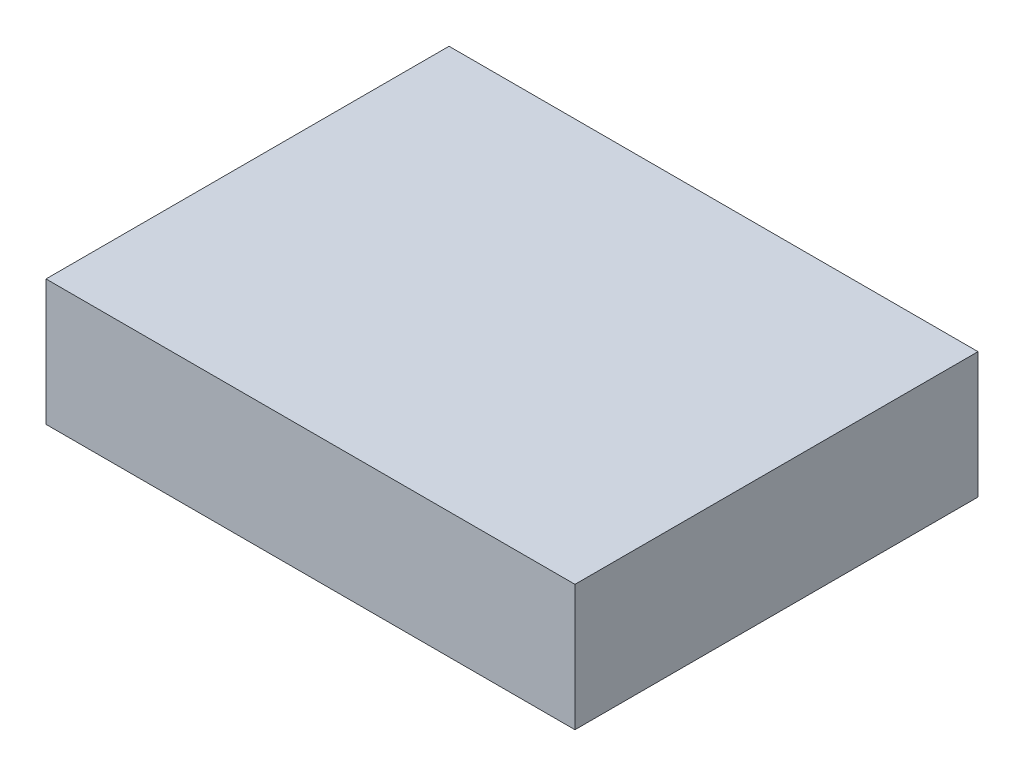
SolidWorks part; units mm, degrees
ref_plane "Front Plane" through (0, 0, 0) normal (0, 0, 1) x (1, 0, 0)
ref_plane "Top Plane" through (0, 0, 0) normal (0, 1, 0) x (1, 0, 0)
ref_plane "Right Plane" through (0, 0, 0) normal (1, 0, 0) x (0, 0, -1)
sketch "Sketch2" plane through (0, 0, 0) normal (0, 1, 0) x (1, 0, 0)
  line L1 (-10.5, -8) -> (10.5, -8)
  line L2 (-10.5, -8) -> (-10.5, 8)
  line L3 (-10.5, 8) -> (10.5, 8)
  line L4 (10.5, -8) -> (10.5, 8)
  line L5 (-10.5, -8) -> (10.5, 8) construction
  line L6 (-10.5, 8) -> (10.5, -8) construction
  point P0 (0, 0)
  dimension "D1" = 21
  dimension "D2" = 16
extrude "Boss-Extrude1" add sketch "Sketch2" along normal blind 5
